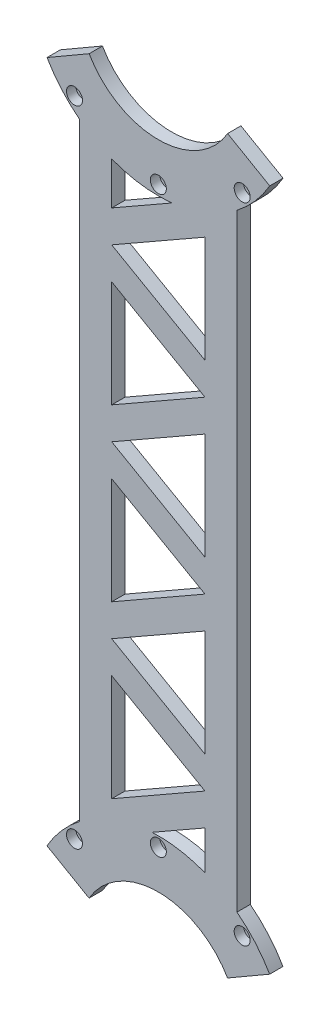
SolidWorks part; units mm, degrees
ref_plane "Front Plane" through (0, 0, 0) normal (0, 0, 1) x (1, 0, 0)
ref_plane "Top Plane" through (0, 0, 0) normal (0, 1, 0) x (1, 0, 0)
ref_plane "Right Plane" through (0, 0, 0) normal (1, 0, 0) x (0, 0, -1)
sketch "Sketch1" plane through (0, 0, 0) normal (0, 0, 1) x (1, 0, 0)
  circle A0 centre (0, 0) radius 48.25
extrude "Boss-Extrude1" add sketch "Sketch1" against normal blind 5 contours A0
sketch "Sketch2" plane through (0, 0, 0) normal (0, 0, 1) x (1, 0, 0)
  line L1 (-63.412, 28.4111) -> (-46.25, 28.4111)
  line L2 (-63.412, 28.4111) -> (-63.412, -28.4111)
  line L3 (-63.412, -28.4111) -> (-46.25, -28.4111)
  line L4 (-46.25, 28.4111) -> (-46.25, -28.4111)
  line L5 (46.25, 28.4111) -> (62.4025, 28.4111)
  line L6 (46.25, 28.4111) -> (46.25, -36.7758)
  line L7 (46.25, -36.7758) -> (62.4025, -36.7758)
  line L8 (62.4025, 28.4111) -> (62.4025, -36.7758)
  dimension "D1" = 92.5
  dimension "D2" = 46.25
extrude "Cut-Extrude1" cut sketch "Sketch2" against normal blind 8 contours L5 L8 L7 L6 | L1 L4 L3 L2
sketch "Sketch3" plane through (0, 0, 0) normal (0, 0, 1) x (1, 0, 0)
  circle A0 centre (0, 0) radius 30
extrude "Cut-Extrude2" cut sketch "Sketch3" against normal blind 8 contours A0
sketch "Sketch4" plane through (0, 0, 0) normal (0, 0, 1) x (1, 0, 0)
  circle A0 centre (-42.5, 0) radius 1.75
  circle A1 centre (0, -44.5) radius 1.75
  circle A2 centre (0, 44.5) radius 1.75
  circle A3 centre (42.5, 0) radius 1.75
  circle A4 centre (-31.4663, -31.4663) radius 1.75
  circle A5 centre (31.4663, -31.4663) radius 1.75
  circle A6 centre (31.4663, 31.4663) radius 1.75
  circle A7 centre (-31.4663, 31.4663) radius 1.75
  point P10 (0, 0)
  point P13 (0, 0)
  point P16 (0, 0)
  point P19 (0, 0)
  point P22 (0, 0)
  point P25 (0, 0)
  dimension "D1" = 42.5
  dimension "D3" = 2
  dimension "D2" = 44.5
  dimension "D4" = 2
  dimension "D5" = 2
  dimension "D6" = 2
  dimension "D7" = 2
  dimension "D8" = 2
extrude "Cut-Extrude3" cut sketch "Sketch4" against normal blind 10
sketch "Sketch9" plane through (0, 0, 0) normal (0, 0, 1) x (1, 0, 0)
  circle A0 centre (-42.5, 0) radius 3
  circle A1 centre (42.5, 0) radius 3
  circle A2 centre (31.4663, 31.4663) radius 3
  circle A3 centre (-31.4663, 31.4663) radius 3
  circle A4 centre (-31.4663, -31.4663) radius 3
  circle A5 centre (31.4663, -31.4663) radius 3
  circle A6 centre (0, -44.5) radius 3
  circle A7 centre (0, 44.5) radius 3
sketch "Sketch10" plane through (0, 0, 0) normal (0, 0, 1) x (1, 0, 0)
  line L0 (0, 0) -> (0, 270) construction
  line L1 (-29.5, 0) -> (-29.5, 270)
  line L2 (29.5, 0) -> (29.5, 270)
  line L3 (-17.5, 39.54) -> (-17.5, 51.54)
  line L4 (-17.5, 267.1329) -> (17.5, 267.1329)
  line L5 (-17.5, 267.1329) -> (-17.5, -10.6365)
  line L6 (-17.5, -10.6365) -> (17.5, -10.6365)
  line L7 (17.5, 267.1329) -> (17.5, -10.6365)
  line L8 (-17.5, 39.54) -> (17.5, 59.54)
  line L9 (-17.5, 51.54) -> (17.5, 71.54)
  line L10 (17.5, 59.54) -> (17.5, 71.54)
  line L11 (17.5, 71.54) -> (17.5, 83.54)
  line L12 (17.5, 71.54) -> (-17.5, 91.54)
  line L13 (17.5, 83.54) -> (-17.5, 103.54)
  line L14 (-17.5, 91.54) -> (-17.5, 103.54)
  line L15 (-17.5, 103.54) -> (-17.5, 115.54)
  line L16 (-17.5, 103.54) -> (17.5, 123.54)
  line L17 (-17.5, 115.54) -> (17.5, 135.54)
  line L18 (17.5, 123.54) -> (17.5, 135.54)
  line L19 (17.5, 135.54) -> (17.5, 147.54)
  line L20 (17.5, 135.54) -> (-17.5, 155.54)
  line L21 (17.5, 147.54) -> (-17.5, 167.54)
  line L22 (-17.5, 155.54) -> (-17.5, 167.54)
  line L23 (-17.5, 167.54) -> (-17.5, 179.54)
  line L24 (-17.5, 167.54) -> (17.5, 187.54)
  line L25 (-17.5, 179.54) -> (17.5, 199.54)
  line L26 (17.5, 187.54) -> (17.5, 199.54)
  line L27 (17.5, 199.54) -> (17.5, 211.54)
  line L28 (17.5, 199.54) -> (-17.5, 219.54)
  line L29 (17.5, 211.54) -> (-17.5, 231.54)
  line L30 (-17.5, 219.54) -> (-17.5, 231.54)
  line L31 (-17.5, 231.54) -> (-17.5, 243.54)
  line L32 (-17.5, 231.54) -> (17.5, 251.54)
  line L33 (-17.5, 243.54) -> (17.5, 263.54)
  line L34 (17.5, 251.54) -> (17.5, 263.54)
  arc A0 (-29.5, 0) -> (29.5, 0) centre (0, 0) ccw
  arc A1 (29.5, 270) -> (-29.5, 270) centre (0, 270) ccw
  point P3 (0, 135)
  dimension "D1" = 12
  dimension "D2" = 12
  dimension "D3" = 12
  dimension "D4" = 20
  dimension "D5" = 12
  dimension "D6" = 20
  dimension "D7" = 12
  dimension "D8" = 20
  dimension "D9" = 12
  dimension "D10" = 20
  dimension "D11" = 12
  dimension "D12" = 20
  dimension "D13" = 12
  dimension "D14" = 20
  dimension "D15" = 12
  dimension "D16" = 20
extrude "Cut-Extrude4" cut sketch "Sketch9" against normal blind 3.5
sketch "Sketch12" plane through (0, 0, 0) normal (0, 0, 1) x (1, 0, 0)
  circle A0 centre (0, 304.453) radius 48.25
  dimension "D1" = 0
extrude "Boss-Extrude4" add sketch "Sketch12" against normal blind 5 separate body contours A0
sketch "Sketch13" plane through (0, 0, 0) normal (0, 0, 1) x (1, 0, 0)
  line L1 (-63.412, 436.9676) -> (-46.25, 436.9676)
  line L2 (-63.412, 436.9676) -> (-63.412, 196.7016)
  line L3 (-63.412, 196.7016) -> (-46.25, 196.7016)
  line L4 (-46.25, 436.9676) -> (-46.25, 196.7016)
  line L5 (46.25, 187.19) -> (62.4025, 187.19)
  line L6 (46.25, 187.19) -> (46.25, 413.3722)
  line L7 (46.25, 413.3722) -> (62.4025, 413.3722)
  line L8 (62.4025, 187.19) -> (62.4025, 413.3722)
  dimension "D1" = 92.5
extrude "Cut-Extrude5" cut sketch "Sketch13" against normal blind 5
sketch "Sketch14" plane through (0, 0, 0) normal (0, 0, 1) x (1, 0, 0)
  circle A0 centre (0, 304.453) radius 30
extrude "Cut-Extrude6" cut sketch "Sketch14" against normal blind 5 contours A0
sketch "Sketch17" plane through (0, 0, 0) normal (0, 0, 1) x (1, 0, 0)
  line L0 (0, 0) -> (-69.3043, 39.9614)
  line L1 (-69.3043, 39.9614) -> (-69.2783, -65.3223)
  line L2 (-69.2783, -65.3223) -> (63.9709, -62.4072)
  line L3 (63.9709, -62.4072) -> (69.2598, 40.0386)
  line L4 (69.2598, 40.0386) -> (0, 0)
  point P2 (0, 0)
  point P3 (0, 0)
  point P4 (46.25, -52.2337)
  point P8 (64.9695, 40.3846)
  point P9 (0, 0)
  point P10 (56.5653, -58.4306)
  point P11 (0, 0)
  point P12 (69.8351, 40.8761)
  point P13 (69.2598, 39.9614)
  dimension "D1" = 120
  dimension "D2" = 80
  dimension "D3" = 80
extrude "Cut-Extrude7" cut sketch "Sketch17" against normal blind 5
sketch "Sketch18" plane through (0, 0, 0) normal (0, 0, 1) x (1, 0, 0)
  line L0 (0, 304.453) -> (-69.2518, 264.4007)
  line L1 (-69.2518, 264.4007) -> (-69.0664, 357.5112)
  line L2 (-69.0664, 357.5112) -> (54.7017, 362.3334)
  line L3 (54.7017, 362.3334) -> (69.3123, 264.5054)
  line L4 (69.3123, 264.5054) -> (0, 304.453)
  point P0 (-69.0664, 264.5054)
  dimension "D1" = 120
  dimension "D2" = 80
  dimension "D3" = 80
extrude "Cut-Extrude8" cut sketch "Sketch18" against normal blind 5
sketch "Sketch19" plane through (0, 0, 0) normal (0, 0, 1) x (1, 0, 0)
  line L0 (0, 0) -> (0, 270) construction
  circle A0 centre (0, 259.953) radius 1.75
  circle A1 centre (0, 304.453) radius 30 construction
  circle A2 centre (-31.4663, 272.9868) radius 1.75
  circle A3 centre (31.4663, 272.9868) radius 1.75
  point P12 (0, 304.453)
  point P15 (0, 304.453)
  dimension "D1" = 44.5
  dimension "D2" = 2
  dimension "D3" = 2
extrude "Cut-Extrude9" cut sketch "Sketch19" against normal blind 5
sketch "Sketch20" plane through (0, 0, 0) normal (0, 0, 1) x (1, 0, 0)
  circle A0 centre (-31.4663, 272.9868) radius 3
  circle A1 centre (0, 259.953) radius 3
  circle A2 centre (31.4663, 272.9868) radius 3
extrude "Cut-Extrude10" cut sketch "Sketch20" against normal blind 3.5
extrude "Boss-Extrude5" add sketch "Sketch10" against normal blind 5
sketch "Sketch21" plane through (0, 0, 0) normal (0, 0, 1) x (1, 0, 0)
  circle A0 centre (0, 304.453) radius 30
extrude "Cut-Extrude11" cut sketch "Sketch21" against normal blind 5
sketch "Sketch22" plane through (0, 0, 0) normal (0, 0, 1) x (1, 0, 0)
  circle A0 centre (31.4663, 272.9868) radius 3
  circle A1 centre (-31.4663, 272.9868) radius 3
extrude "Cut-Extrude12" cut sketch "Sketch22" against normal blind 3.5
